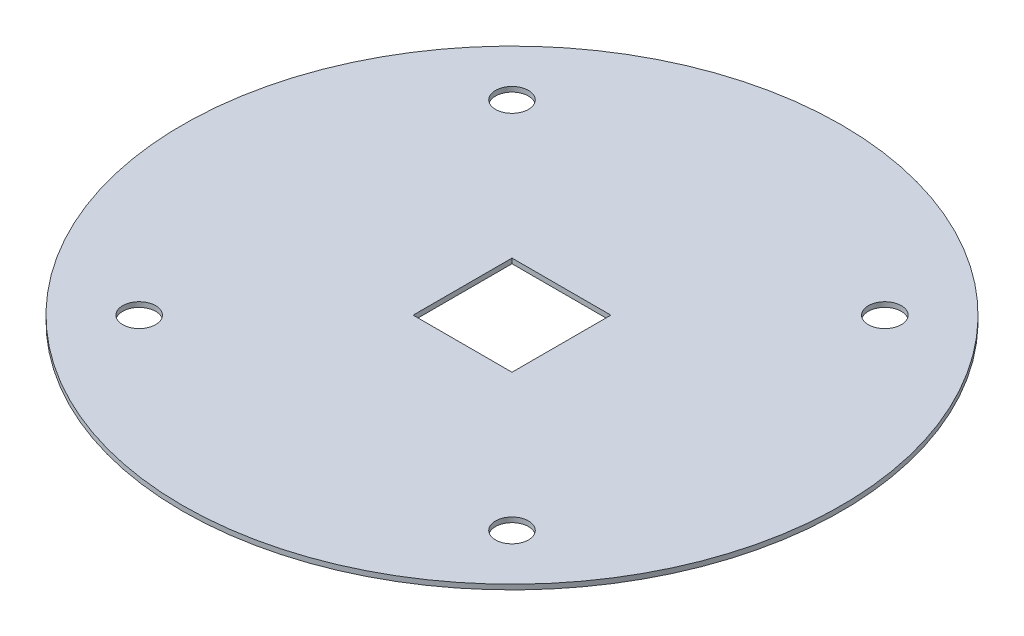
SolidWorks part; units mm, degrees
ref_plane "前视基准面" through (0, 0, 0) normal (0, 0, 1) x (1, 0, 0)
ref_plane "上视基准面" through (0, 0, 0) normal (0, 1, 0) x (1, 0, 0)
ref_plane "右视基准面" through (0, 0, 0) normal (1, 0, 0) x (0, 0, -1)
sketch "草图1" plane through (0, 0, 0) normal (0, 1, 0) x (1, 0, 0)
  line L0 (0, 0) -> (0, 50000) construction
  line L1 (0, 0) -> (50000, 0) construction
  line L2 (0, 0) -> (35355.3391, -35355.3391) construction
  line L3 (0, 0) -> (35355.3391, 35355.3391) construction
  circle A0 centre (0, 0) radius 200
extrude "凸台-拉伸1" add sketch "草图1" along normal blind 3 contours A0
sketch "草图2" plane through (0, 3, 0) normal (0, 1, 0) x (1, 0, 0)
  line L0 (0, 0) -> (0, 50000) construction
  line L1 (0, 0) -> (50000, 0) construction
  line L2 (0, 0) -> (35355.3391, -35355.3391) construction
  line L3 (0, 0) -> (35355.3391, 35355.3391) construction
  circle A0 centre (-113.1371, 113.1371) radius 10
  circle A1 centre (-113.1371, -113.1371) radius 10
  circle A2 centre (113.1371, -113.1371) radius 10
  circle A3 centre (113.1371, 113.1371) radius 10
  dimension "D1" = 160
extrude "切除-拉伸1" cut sketch "草图2" against normal blind 3 contours A0 | A2 | A3 | A1
sketch "草图3" plane through (0, 3, 0) normal (0, 1, 0) x (1, 0, 0)
  line L0 (0, 0) -> (0, 50000) construction
  line L1 (0, 0) -> (50000, 0) construction
  line L3 (-30, 30) -> (30, 30)
  line L4 (-30, 30) -> (-30, -30)
  line L5 (-30, -30) -> (30, -30)
  line L6 (30, 30) -> (30, -30)
extrude "切除-拉伸2" cut sketch "草图3" against normal blind 3 contours L4 L3 L6 L5
